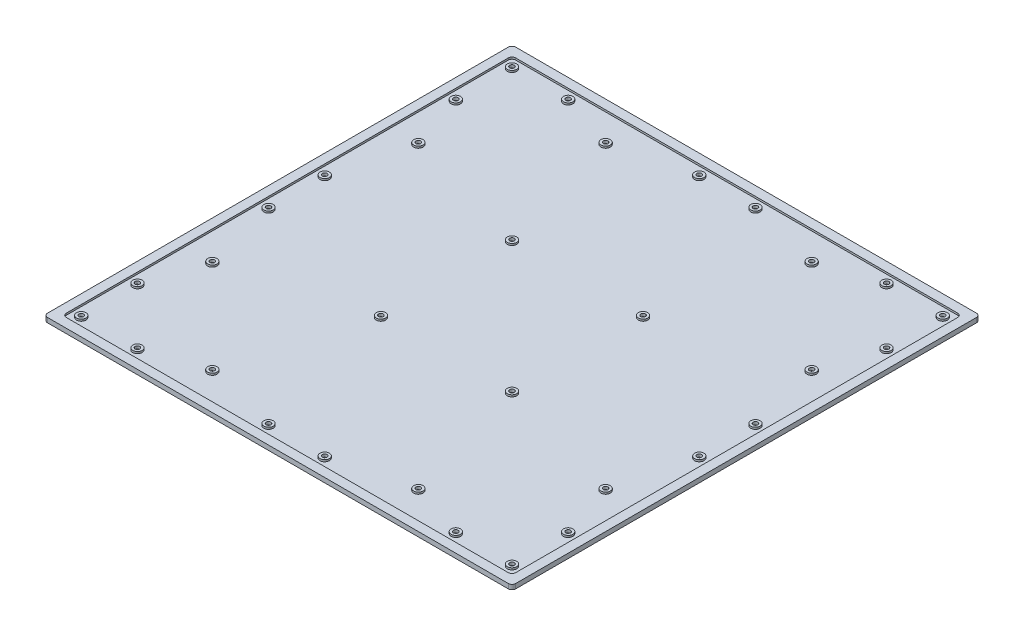
SolidWorks part; units mm, degrees
material "99.5% Aluminum Oxide"
ref_plane "Front Plane" through (0, 0, 0) normal (0, 0, 1) x (1, 0, 0)
ref_plane "Top Plane" through (0, 0, 0) normal (0, 1, 0) x (1, 0, 0)
ref_plane "Right Plane" through (0, 0, 0) normal (1, 0, 0) x (0, 0, -1)
sketch "Sketch1" plane through (0, 0, 0) normal (0, 1, 0) x (1, 0, 0)
  line L1 (-125, -125) -> (125, -125)
  line L2 (-125, -125) -> (-125, 125)
  line L3 (-125, 125) -> (125, 125)
  line L4 (125, -125) -> (125, 125)
  line L5 (-125, -125) -> (125, 125) construction
  line L6 (-125, 125) -> (125, -125) construction
  point P0 (0, 0)
  dimension "D1" = 250
extrude "Boss-Extrude1" add sketch "Sketch1" along normal mid plane 2.5
sketch "Sketch2" plane through (0, 1.25, 0) normal (0, 1, 0) x (1, 0, 0)
  line L0 (-125, 125) -> (-125, -125) construction
  line L1 (-120, -120) -> (120, -120)
  line L2 (-120, -120) -> (-120, 120)
  line L3 (-120, 120) -> (120, 120)
  line L4 (120, -120) -> (120, 120)
  line L5 (-120, -120) -> (120, 120) construction
  line L6 (-120, 120) -> (120, -120) construction
  point P0 (0, 0)
  dimension "D1" = 5
extrude "Cut-Extrude1" cut sketch "Sketch2" against normal blind 1
sketch "Sketch3" plane through (0, 0.25, 0) normal (0, 1, 0) x (1, 0, 0)
  line L0 (-120, 120) -> (-120, -120) construction
  line L1 (-110, 120) -> (-110, -120) construction
  line L2 (-100, 120) -> (-100, -120) construction
  line L3 (-90, 120) -> (-90, -120) construction
  line L4 (-80, 120) -> (-80, -120) construction
  line L5 (-70, 120) -> (-70, -120) construction
  line L6 (-60, 120) -> (-60, -120) construction
  line L7 (-50, 120) -> (-50, -120) construction
  line L8 (-40, 120) -> (-40, -120) construction
  line L9 (-30, 120) -> (-30, -120) construction
  line L10 (-20, 120) -> (-20, -120) construction
  line L11 (-10, 120) -> (-10, -120) construction
  line L12 (0, 120) -> (0, -120) construction
  line L13 (10, 120) -> (10, -120) construction
  line L14 (20, 120) -> (20, -120) construction
  line L15 (30, 120) -> (30, -120) construction
  line L16 (40, 120) -> (40, -120) construction
  line L17 (50, 120) -> (50, -120) construction
  line L18 (60, 120) -> (60, -120) construction
  line L19 (70, 120) -> (70, -120) construction
  line L20 (80, 120) -> (80, -120) construction
  line L21 (90, 120) -> (90, -120) construction
  line L22 (100, 120) -> (100, -120) construction
  line L23 (110, 120) -> (110, -120) construction
  line L24 (120, 120) -> (120, -120) construction
  line L25 (-120, 120) -> (-110, 120) construction
  line L26 (-125, 125) -> (-125, -125) construction
  line L28 (-125, -125) -> (125, -125) construction
  line L29 (0, 0) -> (-15, -115) construction
  line L30 (-35, -35) -> (35, -35) construction
  line L31 (-35, -35) -> (-35, 35) construction
  line L32 (-35, 35) -> (35, 35) construction
  line L33 (35, -35) -> (35, 35) construction
  line L34 (-35, -35) -> (35, 35) construction
  line L35 (-35, 35) -> (35, -35) construction
  circle A0 centre (-115, -115) radius 2.5
  circle A1 centre (-85, -115) radius 2.5
  circle A2 centre (-55, -105) radius 2.5
  circle A3 centre (-15, -115) radius 2.5
  circle A4 centre (15, -115) radius 2.5
  circle A5 centre (55, -105) radius 2.5
  circle A6 centre (85, -115) radius 2.5
  circle A7 centre (-115, 115) radius 2.5
  circle A8 centre (-115, 85) radius 2.5
  circle A9 centre (-105, 55) radius 2.5
  circle A10 centre (-115, 15) radius 2.5
  circle A11 centre (-115, -15) radius 2.5
  circle A12 centre (-105, -55) radius 2.5
  circle A13 centre (-115, -85) radius 2.5
  circle A14 centre (115, 115) radius 2.5
  circle A15 centre (85, 115) radius 2.5
  circle A16 centre (55, 105) radius 2.5
  circle A17 centre (15, 115) radius 2.5
  circle A18 centre (-15, 115) radius 2.5
  circle A19 centre (-55, 105) radius 2.5
  circle A20 centre (-85, 115) radius 2.5
  circle A21 centre (115, -115) radius 2.5
  circle A22 centre (115, -85) radius 2.5
  circle A23 centre (105, -55) radius 2.5
  circle A24 centre (115, -15) radius 2.5
  circle A25 centre (115, 15) radius 2.5
  circle A26 centre (105, 55) radius 2.5
  circle A27 centre (115, 85) radius 2.5
  circle A28 centre (-35, 35) radius 2.5
  circle A29 centre (-35, -35) radius 2.5
  circle A30 centre (35, -35) radius 2.5
  circle A31 centre (35, 35) radius 2.5
  dimension "D5" = 5
  dimension "D2" = 10
  dimension "D3" = 10
  dimension "D4" = 10
  dimension "D6" = 40
  dimension "D7" = 70
  dimension "D8" = 20
  dimension "D9" = 110
  dimension "D11" = 115.9741
  dimension "D12" = 90
  dimension "D1" = 25
  dimension "D10" = 4
extrude "Boss-Extrude2" add sketch "Sketch3" along normal up to surface (1 mm away) up to face at (0, 1.25, 0)
fillet "Fillet1" radius 2 8 edges at (125, 0, 125) (-125, 0, 125) (-125, 0, -125) (125, 0, -125) (-120, 0.75, 120) (120, 0.75, 120) (120, 0.75, -120) (-120, 0.75, -120)
sketch "Sketch4" plane through (0, 1.25, 0) normal (0, 1, 0) x (1, 0, 0)
  circle A0 centre (115, -85) radius 2.5 construction
  circle A1 centre (115, -115) radius 2.5 construction
  circle A2 centre (85, -115) radius 2.5 construction
  circle A3 centre (105, -55) radius 2.5 construction
  circle A4 centre (115, -15) radius 2.5 construction
  circle A5 centre (115, 15) radius 2.5 construction
  circle A6 centre (105, 55) radius 2.5 construction
  circle A7 centre (115, 85) radius 2.5 construction
  circle A8 centre (115, 115) radius 2.5 construction
  circle A9 centre (55, 105) radius 2.5 construction
  circle A10 centre (35, 35) radius 2.5 construction
  circle A11 centre (35, -35) radius 2.5 construction
  circle A12 centre (15, -115) radius 2.5 construction
  circle A13 centre (-15, -115) radius 2.5 construction
  circle A14 centre (-35, -35) radius 2.5 construction
  circle A15 centre (-35, 35) radius 2.5 construction
  circle A16 centre (-55, -105) radius 2.5 construction
  circle A17 centre (-85, -115) radius 2.5 construction
  circle A18 centre (-115, -115) radius 2.5 construction
  circle A19 centre (-115, -85) radius 2.5 construction
  circle A20 centre (-105, -55) radius 2.5 construction
  circle A21 centre (-115, 15) radius 2.5 construction
  circle A22 centre (-15, 115) radius 2.5 construction
  circle A23 centre (-105, 55) radius 2.5 construction
  circle A24 centre (-55, 105) radius 2.5 construction
  circle A25 centre (-85, 115) radius 2.5 construction
  circle A26 centre (-115, 85) radius 2.5 construction
  circle A27 centre (-115, 115) radius 2.5 construction
  circle A28 centre (85, 115) radius 2.5 construction
  circle A29 centre (15, 115) radius 2.5 construction
  circle A30 centre (55, -105) radius 2.5 construction
  circle A31 centre (-115, -15) radius 2.5 construction
  circle A32 centre (115, -85) radius 2.5 construction
  circle A33 centre (115, -115) radius 2.5 construction
  circle A34 centre (85, -115) radius 2.5 construction
  circle A35 centre (105, -55) radius 2.5 construction
  circle A36 centre (115, -15) radius 2.5 construction
  circle A37 centre (115, 15) radius 2.5 construction
  circle A38 centre (105, 55) radius 2.5 construction
  circle A39 centre (115, 85) radius 2.5 construction
  circle A40 centre (115, 115) radius 2.5 construction
  circle A41 centre (55, 105) radius 2.5 construction
  circle A42 centre (35, 35) radius 2.5 construction
  circle A43 centre (35, -35) radius 2.5 construction
  circle A44 centre (15, -115) radius 2.5 construction
  circle A45 centre (-15, -115) radius 2.5 construction
  circle A46 centre (-35, -35) radius 2.5 construction
  circle A47 centre (-35, 35) radius 2.5 construction
  circle A48 centre (-55, -105) radius 2.5 construction
  circle A49 centre (-85, -115) radius 2.5 construction
  circle A50 centre (-115, -115) radius 2.5 construction
  circle A51 centre (-115, -85) radius 2.5 construction
  circle A52 centre (-105, -55) radius 2.5 construction
  circle A53 centre (-115, 15) radius 2.5 construction
  circle A54 centre (-15, 115) radius 2.5 construction
  circle A55 centre (-105, 55) radius 2.5 construction
  circle A56 centre (-55, 105) radius 2.5 construction
  circle A57 centre (-85, 115) radius 2.5 construction
  circle A58 centre (-115, 85) radius 2.5 construction
  circle A59 centre (-115, 115) radius 2.5 construction
  circle A60 centre (85, 115) radius 2.5 construction
  circle A61 centre (15, 115) radius 2.5 construction
  circle A62 centre (55, -105) radius 2.5 construction
  circle A63 centre (-115, -15) radius 2.5 construction
hole_wizard "Tap Drill for M3x0.5 Tap1" positions "3DSketch1" profile "Sketch5" hole size "M3x0.5" standard "ANSI Metric"
sketch3d "3DSketch1"
  point P0 (-115, 1.25, 115)
  point P3 (-85, 1.25, 115)
  point P6 (-115, 1.25, 85)
  point P9 (-105, 1.25, 55)
  point P12 (-115, 1.25, 15)
  point P15 (-115, 1.25, -15)
  point P18 (-115, 1.25, -85)
  point P21 (-105, 1.25, -55)
  point P24 (-115, 1.25, -115)
  point P27 (-85, 1.25, -115)
  point P30 (-55, 1.25, -105)
  point P33 (-15, 1.25, -115)
  point P36 (15, 1.25, -115)
  point P39 (-35, 1.25, -35)
  point P42 (35, 1.25, -35)
  point P45 (-55, 1.25, 105)
  point P48 (-35, 1.25, 35)
  point P51 (35, 1.25, 35)
  point P54 (-15, 1.25, 115)
  point P57 (15, 1.25, 115)
  point P60 (55, 1.25, 105)
  point P63 (85, 1.25, 115)
  point P66 (115, 1.25, 115)
  point P69 (115, 1.25, 85)
  point P72 (105, 1.25, 55)
  point P75 (115, 1.25, 15)
  point P78 (115, 1.25, -15)
  point P81 (105, 1.25, -55)
  point P84 (55, 1.25, -105)
  point P87 (85, 1.25, -115)
  point P90 (115, 1.25, -115)
  point P93 (115, 1.25, -85)
sketch "Sketch5" plane through (-115, 1.25, 115) normal (1, 0, 0) x (0, 0, 1)
  line L0 (0, 0) -> (0, 2.2511)
  line L1 (0, 2.2511) -> (1.25, 1.5)
  line L2 (1.25, 1.5) -> (1.25, 0)
  line L5 (1.25, 0) -> (0, 0)
  line L10 (0, 2.2511) -> (-1.25, 1.5) construction
  line L11 (0, -6.35) -> (0, 107.95) construction
  dimension "Hole Dia." = 2.5
  dimension "Hole Depth" = 1.5
  dimension "Drill Angle" = 118
